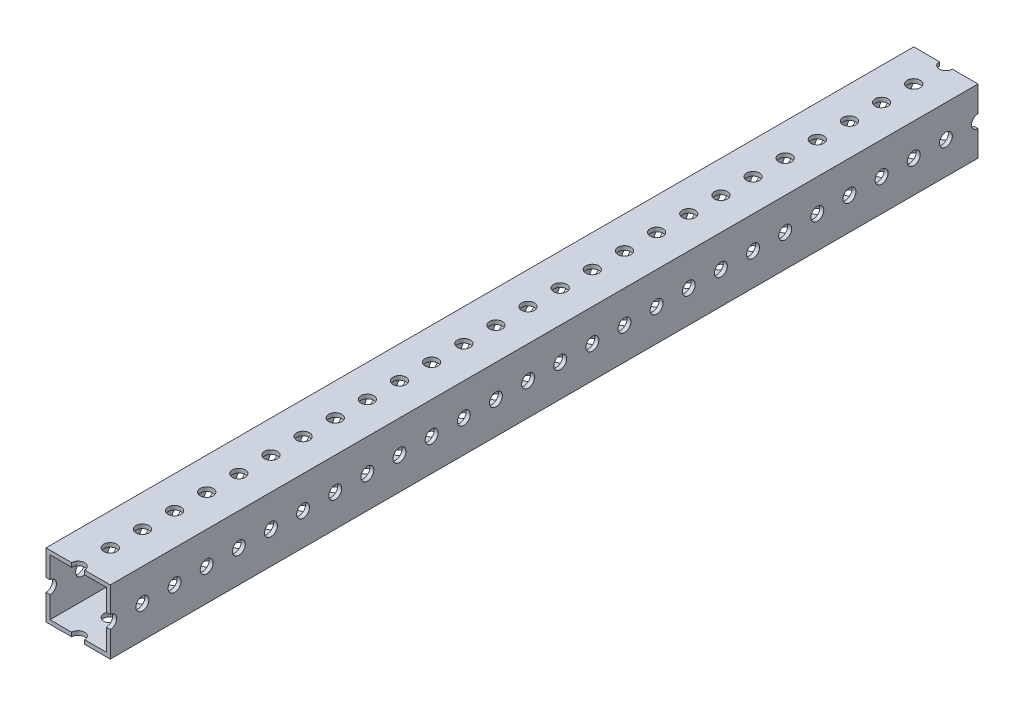
SolidWorks part; units mm, degrees
ref_plane "Front Plane" through (0, 0, 0) normal (0, 0, 1) x (1, 0, 0)
ref_plane "Top Plane" through (0, 0, 0) normal (0, 1, 0) x (1, 0, 0)
ref_plane "Right Plane" through (0, 0, 0) normal (1, 0, 0) x (0, 0, -1)
sketch "Sketch1" plane through (0, 0, 0) normal (0, 0, 1) x (1, 0, 0)
  line L1 (-12.7, 12.7) -> (12.7, 12.7)
  line L2 (-12.7, 12.7) -> (-12.7, -12.7)
  line L3 (-12.7, -12.7) -> (12.7, -12.7)
  line L4 (12.7, 12.7) -> (12.7, -12.7)
  line L5 (-12.7, 12.7) -> (12.7, -12.7) construction
  line L6 (-12.7, -12.7) -> (12.7, 12.7) construction
  line L7 (-11.1125, 11.1125) -> (11.1125, 11.1125)
  line L8 (-11.1125, 11.1125) -> (-11.1125, -11.1125)
  line L9 (-11.1125, -11.1125) -> (11.1125, -11.1125)
  line L10 (11.1125, 11.1125) -> (11.1125, -11.1125)
  line L11 (-11.1125, 11.1125) -> (11.1125, -11.1125) construction
  line L12 (-11.1125, -11.1125) -> (11.1125, 11.1125) construction
  point P0 (0, 0)
  point P6 (0, 0)
  dimension "D1" = 25.4
  dimension "D2" = 25.4
  dimension "D3" = 1.5875
  dimension "D4" = 1.5875
extrude "Boss-Extrude1" add sketch "Sketch1" along normal blind 342.9
sketch "Sketch2" plane through (0, 12.7, 0) normal (0, 1, 0) x (1, 0, 0)
  line L0 (0, 0) -> (0, -12.7) construction
  circle A0 centre (0, 0) radius 2.5527
  circle A1 centre (0, -12.7) radius 2.5527
  circle A2 centre (0, -25.4) radius 2.5527
  circle A3 centre (0, -38.1) radius 2.5527
  circle A4 centre (0, -50.8) radius 2.5527
  circle A5 centre (0, -63.5) radius 2.5527
  circle A6 centre (0, -76.2) radius 2.5527
  circle A7 centre (0, -88.9) radius 2.5527
  circle A8 centre (0, -101.6) radius 2.5527
  circle A9 centre (0, -114.3) radius 2.5527
  circle A10 centre (0, -127) radius 2.5527
  circle A11 centre (0, -139.7) radius 2.5527
  circle A12 centre (0, -152.4) radius 2.5527
  circle A13 centre (0, -165.1) radius 2.5527
  circle A14 centre (0, -177.8) radius 2.5527
  circle A15 centre (0, -190.5) radius 2.5527
  circle A16 centre (0, -203.2) radius 2.5527
  circle A17 centre (0, -215.9) radius 2.5527
  circle A18 centre (0, -228.6) radius 2.5527
  circle A19 centre (0, -241.3) radius 2.5527
  circle A20 centre (0, -254) radius 2.5527
  circle A21 centre (0, -266.7) radius 2.5527
  circle A22 centre (0, -279.4) radius 2.5527
  circle A23 centre (0, -292.1) radius 2.5527
  circle A24 centre (0, -304.8) radius 2.5527
  circle A25 centre (0, -317.5) radius 2.5527
  circle A26 centre (0, -330.2) radius 2.5527
  circle A27 centre (0, -342.9) radius 2.5527
  circle A28 centre (0, -355.6) radius 2.5527
  circle A29 centre (0, -368.3) radius 2.5527
  dimension "D1" = 5.1054
  dimension "D3" = 12.7
  dimension "D2" = 30
extrude "Cut-Extrude1" cut sketch "Sketch2" against normal through all
sketch "Sketch3" plane through (12.7, 0, 0) normal (1, 0, 0) x (0, 0, -1)
  line L0 (0, -12.7) -> (0, 12.7) construction
  line L1 (0, 0) -> (-12.7, 0) construction
  circle A0 centre (0, 0) radius 2.5527
  circle A1 centre (-12.7, 0) radius 2.5527
  circle A2 centre (-25.4, 0) radius 2.5527
  circle A3 centre (-38.1, 0) radius 2.5527
  circle A4 centre (-50.8, 0) radius 2.5527
  circle A5 centre (-63.5, 0) radius 2.5527
  circle A6 centre (-76.2, 0) radius 2.5527
  circle A7 centre (-88.9, 0) radius 2.5527
  circle A8 centre (-101.6, 0) radius 2.5527
  circle A9 centre (-114.3, 0) radius 2.5527
  circle A10 centre (-127, 0) radius 2.5527
  circle A11 centre (-139.7, 0) radius 2.5527
  circle A12 centre (-152.4, 0) radius 2.5527
  circle A13 centre (-165.1, 0) radius 2.5527
  circle A14 centre (-177.8, 0) radius 2.5527
  circle A15 centre (-190.5, 0) radius 2.5527
  circle A16 centre (-203.2, 0) radius 2.5527
  circle A17 centre (-215.9, 0) radius 2.5527
  circle A18 centre (-228.6, 0) radius 2.5527
  circle A19 centre (-241.3, 0) radius 2.5527
  circle A20 centre (-254, 0) radius 2.5527
  circle A21 centre (-266.7, 0) radius 2.5527
  circle A22 centre (-279.4, 0) radius 2.5527
  circle A23 centre (-292.1, 0) radius 2.5527
  circle A24 centre (-304.8, 0) radius 2.5527
  circle A25 centre (-317.5, 0) radius 2.5527
  circle A26 centre (-330.2, 0) radius 2.5527
  circle A27 centre (-342.9, 0) radius 2.5527
  circle A28 centre (-355.6, 0) radius 2.5527
  circle A29 centre (-368.3, 0) radius 2.5527
  dimension "D1" = 5.1054
  dimension "D3" = 12.7
  dimension "D2" = 30
extrude "Cut-Extrude2" cut sketch "Sketch3" against normal through all
